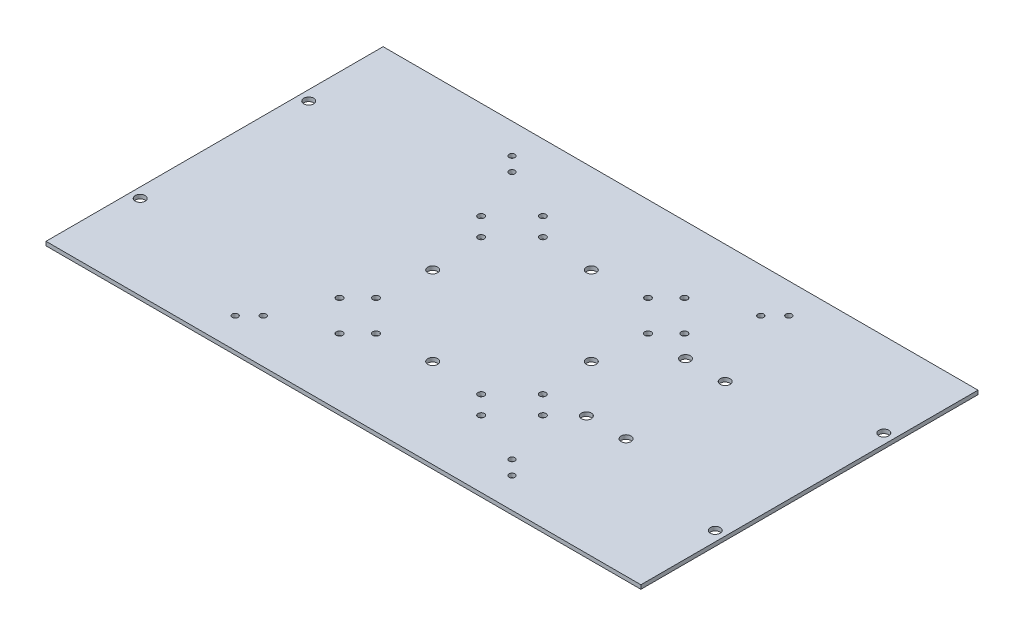
SolidWorks part; units mm, degrees
ref_plane "Front Plane" through (0, 0, 0) normal (0, 0, 1) x (1, 0, 0)
ref_plane "Top Plane" through (0, 0, 0) normal (0, 1, 0) x (1, 0, 0)
ref_plane "Right Plane" through (0, 0, 0) normal (1, 0, 0) x (0, 0, -1)
sketch "Sketch1" plane through (0, 0, 0) normal (0, 1, 0) x (1, 0, 0)
  line L4 (-135, 85) -> (-135, -85)
  line L8 (165, 85) -> (-135, 85)
  line L10 (165, -85) -> (165, 85)
  line L11 (165, -85) -> (-135, -85)
  point P0 (0, 0)
extrude "Boss-Extrude3" add sketch "Sketch1" along normal blind 2
sketch "Sketch3" plane through (0, 2, 0) normal (0, 1, 0) x (1, 0, 0)
  circle A0 centre (15, 40) radius 2.5
  circle A1 centre (55, 0) radius 2.5
  circle A2 centre (15, -40) radius 2.5
  circle A3 centre (-25, 0) radius 2.5
  point P13 (0, 0)
  point P21 (15, 0)
  dimension "D1" = 4
extrude "Cut-Extrude5" cut sketch "Sketch3" against normal blind 120
sketch "Sketch4" plane through (0, 2, 0) normal (0, 1, 0) x (1, 0, 0)
  line L2 (97.5, 0) -> (97.5, -25) construction
  line L3 (97.5, -25) -> (77.5, -25) construction
  circle A0 centre (97.5, -25) radius 2.5
  circle A1 centre (77.5, -25) radius 2.5
  circle A2 centre (97.5, 25) radius 2.5
  circle A3 centre (77.5, 25) radius 2.5
extrude "Cut-Extrude6" cut sketch "Sketch4" against normal blind 10
sketch "Sketch5" plane through (0, 2, 0) normal (0, 1, 0) x (1, 0, 0)
  line L0 (-23.8909, -38.8909) -> (-16.1127, -46.669) construction
  line L1 (-16.1127, -46.669) -> (-11.5165, -42.0729) construction
  line L2 (15, 0) -> (-23.8909, -38.8909) construction
  circle A0 centre (-11.5165, -42.0729) radius 1.6
  circle A1 centre (-20.7089, -51.2652) radius 1.6
  circle A2 centre (-36.2652, -35.7089) radius 1.6
  circle A3 centre (-27.0729, -26.5165) radius 1.6
  circle A4 centre (-27.0729, 26.5165) radius 1.6
  circle A5 centre (-36.2652, 35.7089) radius 1.6
  circle A6 centre (-11.5165, 42.0729) radius 1.6
  circle A7 centre (-20.7089, 51.2652) radius 1.6
  circle A8 centre (41.5165, 42.0729) radius 1.6
  circle A9 centre (50.7089, 51.2652) radius 1.6
  circle A10 centre (57.0729, 26.5165) radius 1.6
  circle A11 centre (66.2652, 35.7089) radius 1.6
  circle A12 centre (57.0729, -26.5165) radius 1.6
  circle A13 centre (66.2652, -35.7089) radius 1.6
  circle A14 centre (41.5165, -42.0729) radius 1.6
  circle A15 centre (50.7089, -51.2652) radius 1.6
  point P38 (15, 0)
  point P39 (15, 0)
  point P40 (15, 0)
  dimension "D1" = 4
extrude "Cut-Extrude7" cut sketch "Sketch5" against normal blind 10
sketch "Sketch6" plane through (0, 2, 0) normal (0, 1, 0) x (1, 0, 0)
  line L0 (15, 0) -> (-179.4382, 0) construction
  line L1 (-135, 0) -> (-135, 42.5) construction
  line L2 (-135, 85) -> (-135, -85) construction
  line L3 (-135, 42.5) -> (-130, 42.5) construction
  line L4 (15, 0) -> (15, 145.5235) construction
  circle A0 centre (-130, 42.5) radius 2.5
  circle A1 centre (-130, -42.5) radius 2.5
  circle A2 centre (160, 42.5) radius 2.5
  circle A3 centre (160, -42.5) radius 2.5
extrude "Cut-Extrude8" cut sketch "Sketch6" against normal blind 64
sketch "Sketch8" plane through (0, 2, 0) normal (0, 1, 0) x (1, 0, 0)
  line L1 (-135, -85) -> (165, -85) construction
  line L2 (15, -85) -> (15, 0) construction
  line L3 (15, 0) -> (79.5083, 0) construction
  line L4 (81.27, 66.27) -> (84.8056, 69.8056) construction
  line L5 (81.27, 66.27) -> (77.7345, 62.7345) construction
  circle A0 centre (-47.7345, 62.7345) radius 1.5
  circle A1 centre (84.8056, 69.8056) radius 1.5
  circle A2 centre (77.7345, 62.7345) radius 1.5
  circle A3 centre (-54.8056, 69.8056) radius 1.5
  circle A4 centre (-54.8056, -69.8056) radius 1.5
  circle A5 centre (-47.7345, -62.7345) radius 1.5
  circle A6 centre (77.7345, -62.7345) radius 1.5
  circle A7 centre (84.8056, -69.8056) radius 1.5
extrude "Cut-Extrude10" cut sketch "Sketch8" against normal blind 10
